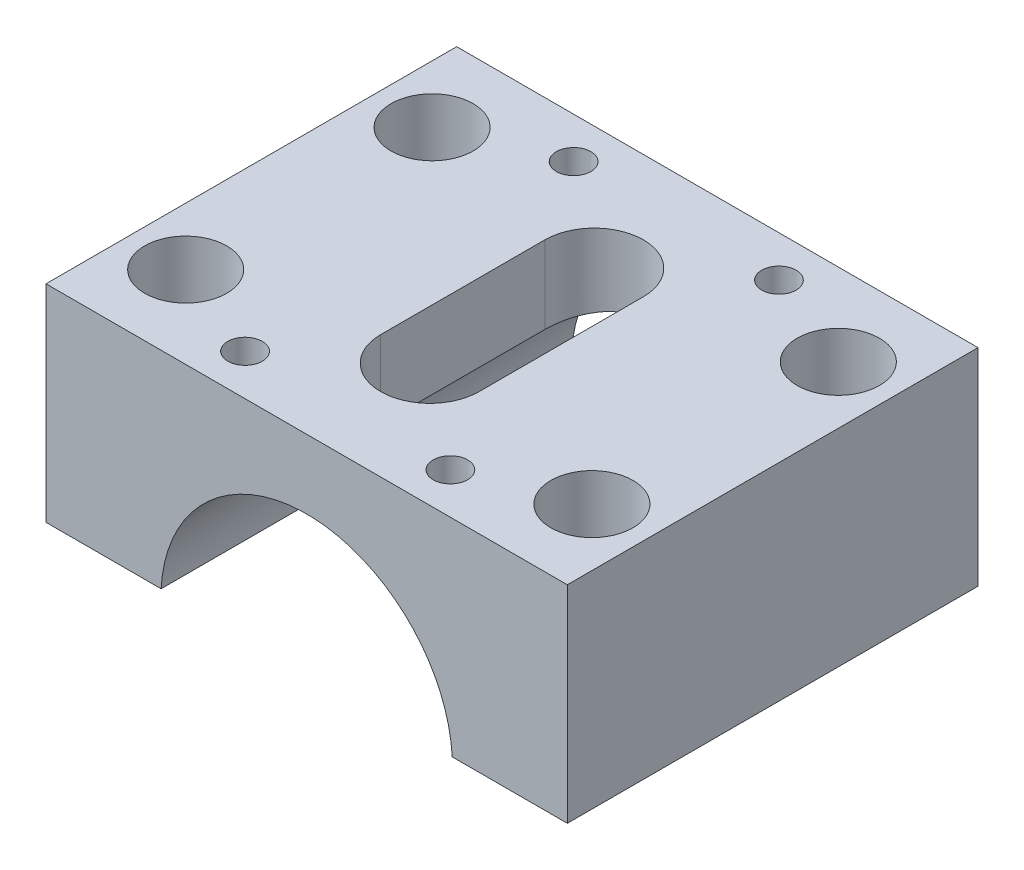
SolidWorks part; units mm, degrees
ref_plane "Front" through (0, 0, 0) normal (0, 0, 1) x (1, 0, 0)
ref_plane "Top" through (0, 0, 0) normal (0, 1, 0) x (1, 0, 0)
ref_plane "Right" through (0, 0, 0) normal (1, 0, 0) x (0, 0, -1)
sketch "Sketch1" plane through (0, 0, 0) normal (0, 0, 1) x (1, 0, 0)
  line L0 (-31.75, 0) -> (31.75, 0) construction
  line L1 (-31.7342, 1) -> (-17.7218, 1)
  line L2 (-31.75, 1) -> (31.75, 1) construction
  line L3 (17.7218, 1) -> (31.7342, 1)
  arc A0 (31.7342, 1) -> (-31.7342, 1) centre (0, 0) ccw
  arc A1 (17.7218, 1) -> (-17.7218, 1) centre (0, 0) ccw
  dimension "D1" = 35.5
  dimension "D2" = 63.5
  dimension "D3" = 1
extrude "Boss-Extrude1" add sketch "Sketch1" along normal blind 50
sketch "Sketch2" plane through (0, 1, 0) normal (0, -1, 0) x (-1, 0, 0)
  line L0 (24.728, -50) -> (24.728, 0) construction
  line L1 (31.7342, -50) -> (17.7218, -50) construction
  line L2 (31.7342, 0) -> (17.7218, 0) construction
  line L3 (-24.728, -50) -> (-24.728, 0) construction
  line L4 (-17.7218, -50) -> (-31.7342, -50) construction
  line L5 (-17.7218, 0) -> (-31.7342, 0) construction
  line L6 (0, -50) -> (0, 0) construction
  line L7 (-17.7218, -50) -> (17.7218, -50) construction
  circle A0 centre (24.728, -40) radius 1
  circle A1 centre (24.728, -10) radius 1
  circle A2 centre (-24.728, -10) radius 1
  circle A3 centre (-24.728, -40) radius 1
  dimension "D1" = 10
  dimension "D2" = 10
  dimension "D3" = 2
sketch "Sketch9" plane through (0, 0, 50) normal (0, 0, 1) x (1, 0, 0)
  line L2 (-31.7342, 1) -> (-31.7342, 31.75)
  line L3 (-31.7342, 31.75) -> (31.7342, 31.75)
  line L4 (31.7342, 1) -> (31.7342, 31.75)
  line L5 (-31.7342, 1) -> (31.7342, 31.75) construction
  line L6 (-31.7342, 31.75) -> (31.7342, 1) construction
  arc A0 (31.7342, 1) -> (-31.7342, 1) centre (0, 0) ccw construction
  arc A1 (31.7342, 1) -> (-31.7342, 1) centre (0, 0) ccw
  point P4 (0, 16.375)
  point P6 (0, 0)
  arc M2 (31.7342, 1) -> (-31.7342, 1) centre (0, 0) ccw
extrude "Boss-Extrude2" add sketch "Sketch9" against normal up to surface (50 mm away) contours L4 L3 M2 | L3 L2 M2 up to face at (0, 12.875, 0)
hole_wizard "Ø5.0mm Clearance Dowel Hole1" positions "3DSketch1" profile "Sketch3" hole size "Ø5.0" standard "ANSI Metric" end condition up to next
sketch3d "3DSketch1"
  point P0 (-24.728, 1, 40)
  point P3 (-24.728, 1, 10)
  point P6 (24.728, 1, 40)
  point P9 (24.728, 1, 10)
sketch "Sketch3" plane through (-24.728, 1, 40) normal (1, 0, 0) x (0, 0, -1)
  line L0 (0, 0) -> (0, 30.75)
  line L1 (0, 30.75) -> (2.5, 30.75)
  line L2 (2.5, 30.75) -> (2.5, 0)
  line L5 (2.5, 0) -> (0, 0)
  line L11 (0, -6.35) -> (0, 107.95) construction
  dimension "Thru Hole Dia." = 5
  dimension "Thru Hole Depth" = 30.75
ref_plane "Plane1" through (0, 4, 0) normal (0, -1, 0) x (-1, 0, 0)
sketch "Sketch4" plane through (0, 4, 0) normal (0, -1, 0) x (-1, 0, 0)
  circle A0 centre (24.728, -40) radius 5
  circle A1 centre (24.728, -10) radius 5
  circle A2 centre (-24.728, -10) radius 5
  circle A3 centre (-24.728, -40) radius 5
  dimension "D1" = 10
extrude "Cut-Extrude1" cut sketch "Sketch4" against normal up to next
sketch "Sketch5" plane through (0, 1, 0) normal (0, -1, 0) x (-1, 0, 0)
  line L0 (0, -50) -> (0, 0) construction
  line L1 (-17.7218, -50) -> (17.7218, -50) construction
  line L2 (0, -35) -> (0, -15) construction
  line L3 (-6, -35) -> (-6, -15)
  line L4 (6, -35) -> (6, -15)
  arc A1 (-6, -35) -> (6, -35) centre (0, -35) ccw
  arc A2 (6, -15) -> (-6, -15) centre (0, -15) ccw
  point P9 (0, -25)
  dimension "D1" = 12
  dimension "D2" = 20
extrude "Cut-Extrude2" cut sketch "Sketch5" against normal up to next
sketch "Sketch6" plane through (0, 0, 50) normal (0, 0, 1) x (1, 0, 0)
  line L0 (18, 26.1546) -> (-18, 26.1546)
  line L1 (-31.7342, 1) -> (-31.7342, 31.75) construction
  line L2 (-31.7342, 26.1546) -> (31.7342, 26.1546)
  line L3 (-31.7342, 26.1546) -> (-31.7342, 31.75)
  line L4 (-31.7342, 31.75) -> (31.7342, 31.75)
  line L5 (31.7342, 26.1546) -> (31.7342, 31.75)
  line L6 (-31.7342, 26.1546) -> (31.7342, 31.75) construction
  line L7 (-31.7342, 31.75) -> (31.7342, 26.1546) construction
  arc A1 (18, 26.1546) -> (-18, 26.1546) centre (0, 0) ccw
  point P7 (0, 28.9523)
  line M7 (31.7342, 1) -> (31.7342, 31.75)
  line M8 (31.7342, 31.75) -> (-31.7342, 31.75)
  line M9 (-31.7342, 31.75) -> (-31.7342, 1)
  dimension "D1" = 36
extrude "Cut-Extrude3" cut sketch "Sketch6" against normal through all contours A1 L2 M7 M8 | L0 A1 | A1 L4 L2 M9
sketch "Sketch7" plane through (0, 26.1546, 0) normal (0, 1, 0) x (1, 0, 0)
  line L0 (0, -50) -> (0, 0) construction
  line L1 (-12.5, -45) -> (12.5, -45) construction
  line L2 (-12.5, -45) -> (-12.5, -5) construction
  line L3 (-12.5, -5) -> (12.5, -5) construction
  line L4 (12.5, -45) -> (12.5, -5) construction
  line L5 (-12.5, -45) -> (12.5, -5) construction
  line L6 (-12.5, -5) -> (12.5, -45) construction
  circle A0 centre (12.5, -5) radius 0.75
  circle A1 centre (-12.5, -5) radius 0.75
  circle A2 centre (12.5, -45) radius 0.75
  circle A3 centre (-12.5, -45) radius 0.75
  point P0 (0, -25)
  dimension "D3" = 1.5
  dimension "D1" = 40
  dimension "D2" = 25
hole_wizard "Tap Drill for M5x0.8 Tap1" positions "3DSketch2" profile "Sketch8" hole size "M5x0.8" standard "ANSI Metric"
sketch3d "3DSketch2"
  point P0 (-12.5, 26.1546, 5)
  point P3 (-12.5, 26.1546, 45)
  point P6 (12.5, 26.1546, 45)
  point P9 (12.5, 26.1546, 5)
sketch "Sketch8" plane through (-12.5, 26.1546, 5) normal (1, 0, 0) x (0, 0, 1)
  line L0 (0, 0) -> (0, 9.2618)
  line L1 (0, 9.2618) -> (2.1, 8)
  line L2 (2.1, 8) -> (2.1, 0)
  line L5 (2.1, 0) -> (0, 0)
  line L10 (0, 9.2618) -> (-2.1, 8) construction
  line L11 (0, -6.35) -> (0, 107.95) construction
  dimension "Hole Dia." = 4.2
  dimension "Hole Depth" = 8
  dimension "Drill Angle" = 118
